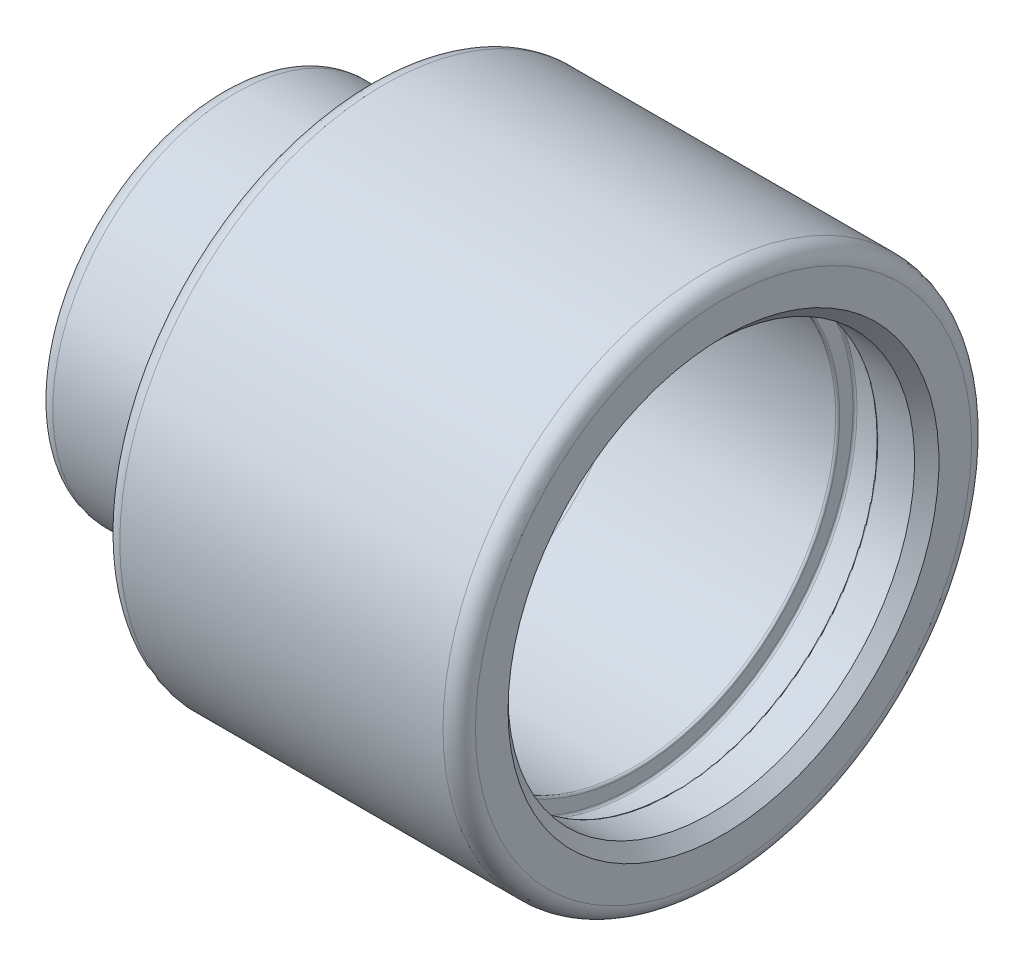
SolidWorks part; units mm, degrees
ref_plane "Front Plane" through (0, 0, 0) normal (0, 0, 1) x (1, 0, 0)
ref_plane "Top Plane" through (0, 0, 0) normal (0, 1, 0) x (1, 0, 0)
ref_plane "Right Plane" through (0, 0, 0) normal (1, 0, 0) x (0, 0, -1)
sketch "Sketch1" plane through (0, 0, 0) normal (0, 0, 1) x (1, 0, 0)
  line L0 (-27.6897, 7.62) -> (-24.5147, 7.62)
  line L1 (-24.5147, 7.62) -> (-24.5147, 8.763)
  line L2 (-24.5147, 8.763) -> (-22.1271, 8.763)
  line L3 (-22.1271, 8.763) -> (-22.1271, 7.62)
  line L4 (-22.1271, 7.62) -> (-15.2437, 7.62)
  line L5 (-15.2437, 7.62) -> (-15.2437, 12.7)
  line L6 (-15.2437, 12.7) -> (-1.7563, 12.7)
  line L7 (-1.7563, 12.7) -> (-1.7563, 13.7795)
  line L8 (-1.7563, 13.7795) -> (0.6313, 13.7795)
  line L9 (0.6313, 13.7795) -> (0.6313, 12.7)
  line L10 (0.6313, 12.7) -> (3.8063, 12.7)
  line L11 (3.8063, 12.7) -> (3.8063, 16.51)
  line L12 (3.8063, 16.51) -> (-18.4187, 16.51)
  line L13 (-18.4187, 16.51) -> (-18.4187, 11.43)
  line L14 (-18.4187, 11.43) -> (-27.6897, 11.43)
  line L15 (-27.6897, 11.43) -> (-27.6897, 7.62)
  line L16 (-425.2079, 0) -> (20835.1888, 0) construction
  point P17 (-0.5625, 13.7795)
  dimension "D1" = 15.24
  dimension "D2" = 25.4
  dimension "D3" = 27.559
  dimension "D4" = 2.3876
  dimension "D5" = 2.3876
  dimension "D6" = 17.526
  dimension "D7" = 22.86
  dimension "D8" = 33.02
  dimension "D9" = 19.05
  dimension "D10" = 3.175
  dimension "D11" = 3.175
  dimension "D12" = 12.446
  dimension "D13" = 3.175
  dimension "D14" = 1.0795
  dimension "D15" = 1.143
revolve "Revolve1" add sketch "Sketch1" angle 360 about L16
chamfer "Chamfer1" distance 0.762 angle 45 2 edges at (-27.6897, 0, 7.62) (3.8063, 0, 12.7)
fillet "Fillet1" radius 1.016 4 edges at (3.8063, 0, 16.51) (-18.4187, 0, 16.51) (-18.4187, 0, 11.43) (-27.6897, 0, 11.43)
fillet "Fillet2" radius 1.524 1 edges at (-15.2437, 0, 7.62)
fillet "Fillet3" radius 0.762 1 edges at (-15.2437, 0, 12.7)
fillet "Fillet4" radius 0.127 8 edges at (-24.5147, 0, 7.62) (-24.5147, 0, 8.763) (-22.1271, 0, 8.763) (-22.1271, 0, 7.62) (0.6313, 0, 13.7795) (0.6313, 0, 12.7) (-1.7563, 0, 12.7) (-1.7563, 0, 13.7795)
